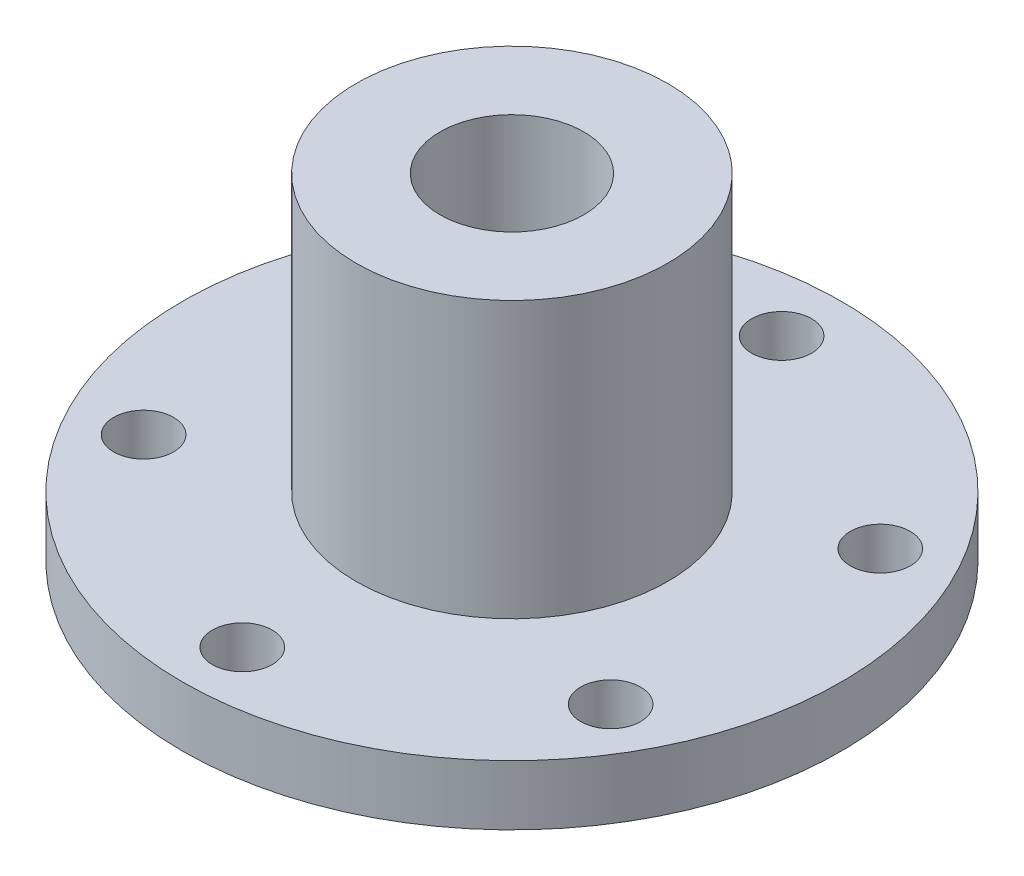
SolidWorks part; units mm, degrees
material "6061 合金"
ref_plane "前视基准面" through (0, 0, 0) normal (0, 0, 1) x (1, 0, 0)
ref_plane "上视基准面" through (0, 0, 0) normal (0, 1, 0) x (1, 0, 0)
ref_plane "右视基准面" through (0, 0, 0) normal (1, 0, 0) x (0, 0, -1)
other "Configuration Table"
sketch "草图1" plane through (0, 0, 0) normal (0, 1, 0) x (1, 0, 0)
  circle A0 centre (0, 0) radius 27.5
  dimension "D1" = 55
extrude "凸台-拉伸1" add sketch "草图1" along normal blind 5
sketch "草图2" plane through (0, 0, 0) normal (0, -1, 0) x (1, 0, 0)
  circle A0 centre (0, 0) radius 10
  dimension "D1" = 20
extrude "凸台-拉伸2" add sketch "草图2" along normal blind 3
sketch "草图3" plane through (0, 5, 0) normal (0, 1, 0) x (1, 0, 0)
  circle A0 centre (0, 0) radius 13
  dimension "D1" = 26
extrude "凸台-拉伸3" add sketch "草图3" along normal blind 23
sketch "草图4" plane through (0, 28, 0) normal (0, 1, 0) x (1, 0, 0)
  circle A0 centre (0, 0) radius 6
  dimension "D1" = 12
extrude "切除-拉伸1" cut sketch "草图4" against normal blind 22
sketch "草图5" plane through (0, -3, 0) normal (0, -1, 0) x (1, 0, 0)
  circle A0 centre (0, 0) radius 7.75
  dimension "D1" = 15.5
extrude "切除-拉伸2" cut sketch "草图5" against normal blind 2
sketch "草图6" plane through (0, -1, 0) normal (0, -1, 0) x (1, 0, 0)
  circle A0 centre (0, 0) radius 3
  dimension "D1" = 6
extrude "切除-拉伸3" cut sketch "草图6" against normal through all
sketch "草图7" plane through (0, 0, 0) normal (0, -1, 0) x (1, 0, 0)
  circle A0 centre (0, 0) radius 22.5 construction
  circle A1 centre (0, 22.5) radius 2.5
  circle A2 centre (19.4856, 11.25) radius 2.5
  circle A3 centre (19.4856, -11.25) radius 2.5
  circle A4 centre (0, -22.5) radius 2.5
  circle A5 centre (-19.4856, -11.25) radius 2.5
  circle A6 centre (-19.4856, 11.25) radius 2.5
  point P5 (0, 0)
  point P6 (-0.3781, -31.2388)
  point P7 (0, 0)
  point P18 (0, 0)
  dimension "D1" = 45
  dimension "D2" = 5
  dimension "D3" = 6
extrude "切除-拉伸4" cut sketch "草图7" against normal through all
